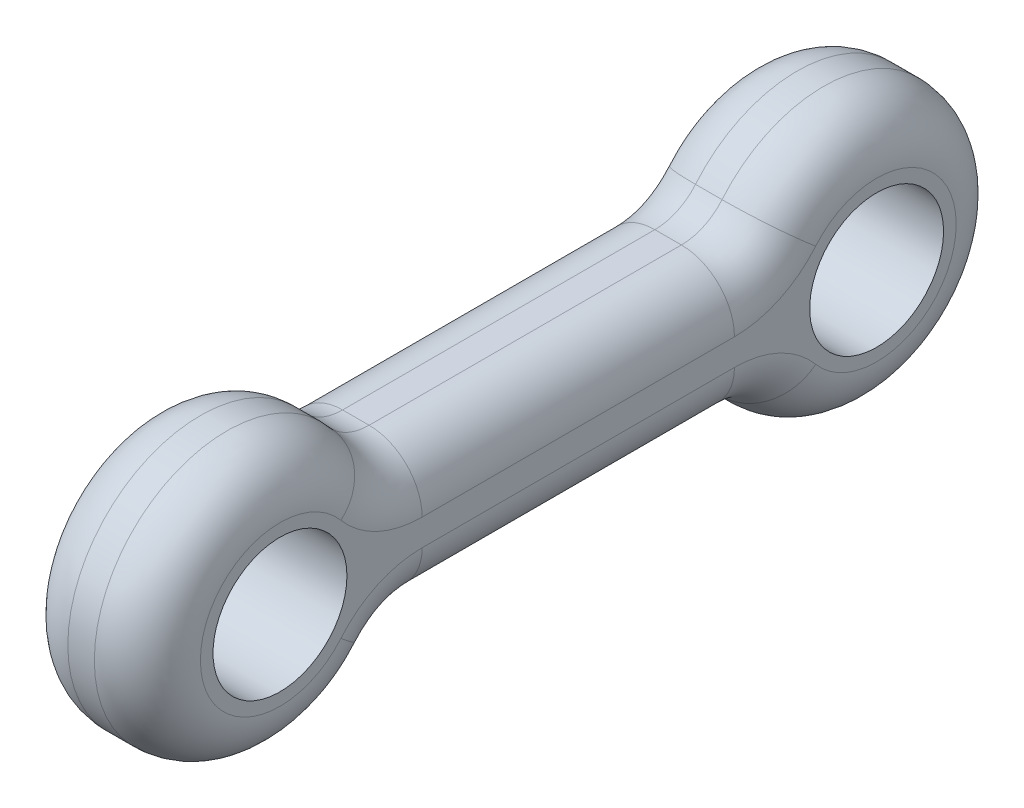
SolidWorks part; units mm, degrees
ref_plane "Front Plane" through (0, 0, 0) normal (0, 0, 1) x (1, 0, 0)
ref_plane "Top Plane" through (0, 0, 0) normal (0, 1, 0) x (1, 0, 0)
ref_plane "Right Plane" through (0, 0, 0) normal (1, 0, 0) x (0, 0, -1)
sketch "Sketch3" plane through (0, 0, 0) normal (1, 0, 0) x (0, 0, -1)
  line L0 (0, 0) -> (-90, 0) construction
  line L2 (0, 0) -> (-90, 0) construction
  line L3 (-17.3205, -10) -> (-72.6795, -10)
  line L4 (-17.3205, 10) -> (-72.6795, 10)
  arc A2 (-72.6795, 10) -> (-72.6795, -10) centre (-90, 0) ccw
  arc A3 (-17.3205, -10) -> (-17.3205, 10) centre (0, 0) ccw
  point P5 (-52.9112, 0)
  dimension "D1" = 90
  dimension "D3" = 20
  dimension "D4" = 20
extrude "Boss-Extrude2" add sketch "Sketch3" along normal blind 20
sketch "Sketch4" plane through (0, 0, 0) normal (1, 0, 0) x (0, 0, -1)
  circle A0 centre (-90, 0) radius 10.1
  dimension "D1" = 20.2
sketch "Sketch5" plane through (0, 0, 0) normal (1, 0, 0) x (0, 0, -1)
  circle A0 centre (0, 0) radius 10.1
  dimension "D1" = 20.2
extrude "Cut-Extrude1" cut sketch "Sketch4" along normal blind 20
extrude "Cut-Extrude2" cut sketch "Sketch5" along normal blind 20
fillet "Fillet1" radius 8 12 edges at (20, 10, 45) (0, 10, 45) (20, -10, 45) (0, -10, 45) (20, 0, -20) (0, 0, -20) (20, 0, 110) (0, 0, 110) (10, -10, 17.3205) (10, 10, 17.3205) (10, 10, 72.6795) (10, -10, 72.6795)
scale "Scale1" scale about origin uniform scaling yes scale factor 0.5
